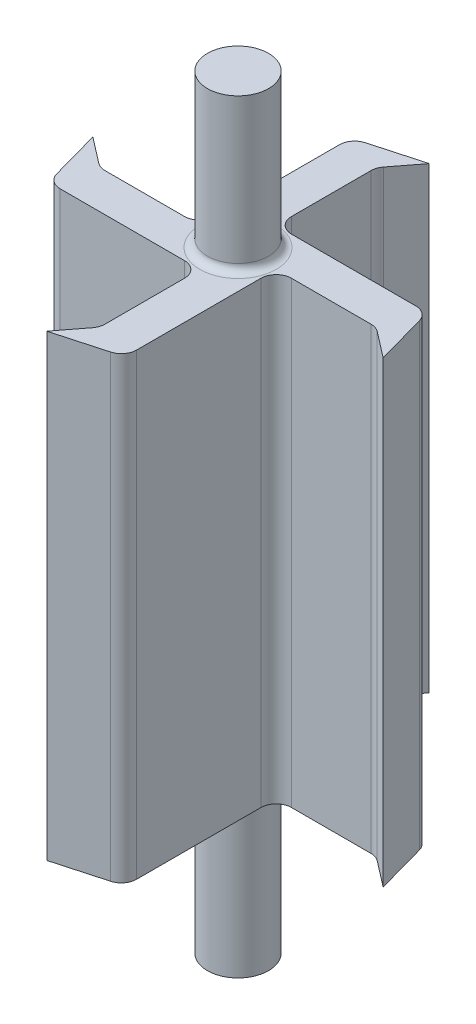
SolidWorks part; units mm, degrees
ref_plane "Front Plane" through (0, 0, 0) normal (0, 0, 1) x (1, 0, 0)
ref_plane "Top Plane" through (0, 0, 0) normal (0, 1, 0) x (1, 0, 0)
ref_plane "Right Plane" through (0, 0, 0) normal (1, 0, 0) x (0, 0, -1)
sketch "Sketch2" plane through (0, 0, 0) normal (0, 1, 0) x (1, 0, 0)
  line L0 (0, 6.4945) -> (0, -6.6178) construction
  line L1 (-6.913, 0) -> (8.4022, 0) construction
  line L2 (-5, 0) -> (-5, 19.7908)
  line L3 (3.0178, 22.0167) -> (-5, 19.7908)
  line L5 (0, 18.0961) -> (3.0178, 22.0167)
  line L7 (0, 18.0961) -> (0, 5)
  line L8 (0, 5) -> (19.7908, 5)
  line L9 (22.0167, -3.0178) -> (19.7908, 5)
  line L10 (18.0961, 0) -> (22.0167, -3.0178)
  line L11 (18.0961, 0) -> (5, 0)
  line L12 (5, 0) -> (5, -19.7908)
  line L13 (-3.0178, -22.0167) -> (5, -19.7908)
  line L14 (0, -18.0961) -> (-3.0178, -22.0167)
  line L15 (0, -18.0961) -> (0, -5)
  line L16 (0, -5) -> (-19.7908, -5)
  line L17 (-22.0167, 3.0178) -> (-19.7908, -5)
  line L18 (-18.0961, 0) -> (-22.0167, 3.0178)
  line L19 (-18.0961, 0) -> (-5, 0)
  circle A0 centre (0, 0) radius 5
  point P26 (0, -0.2913)
  point P27 (0, 0)
  point P32 (0, 0)
  dimension "D1" = 5
  dimension "D5" = 10
  dimension "D3" = 8.321
  dimension "D2" = 19.7908
  dimension "D4" = 4
extrude "Boss-Extrude1" add sketch "Sketch2" along normal blind 60
fillet "Fillet1" radius 2 12 edges at (-5, 30, 0) (0, 30, 18.0961) (-19.7908, 30, 5) (-18.0961, 30, 0) (0, 30, -5) (5, 30, 0) (5, 30, 19.7908) (0, 30, 5) (18.0961, 30, 0) (19.7908, 30, -5) (0, 30, -18.0961) (-5, 30, -19.7908)
sketch "Sketch3" plane through (0, 60, 0) normal (0, 1, 0) x (1, 0, 0)
  circle A0 centre (0, 0) radius 1.8701
extrude "Cut-Extrude1" cut sketch "Sketch3" against normal up to surface (60 mm away) up to face at (0, 0, 0)
ref_plane "Plane1" through (0, 30, 0) normal (0, 1, 0) x (1, 0, 0)
sketch "Sketch4" plane through (0, 30, 0) normal (0, 1, 0) x (1, 0, 0)
  circle A0 centre (0, 0) radius 4
extrude "Boss-Extrude2" add sketch "Sketch4" along normal mid plane 100
fillet "Fillet2" radius 1 2 edges at (0, 60, 4) (0, 0, 4)
